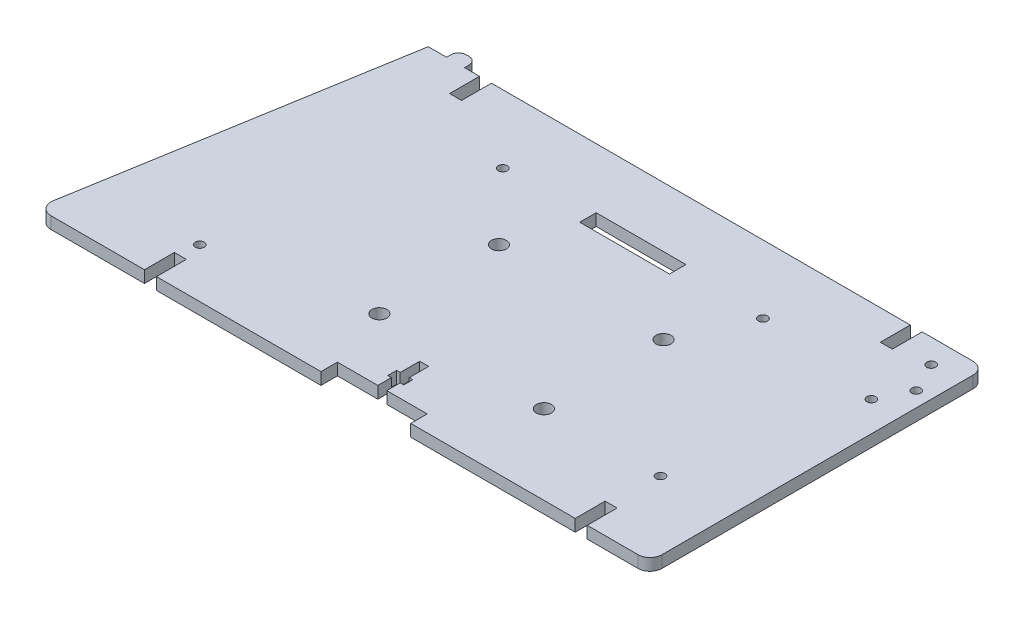
SolidWorks part; units mm, degrees
ref_plane "Front Plane" through (0, 0, 0) normal (0, 0, 1) x (1, 0, 0)
ref_plane "Top Plane" through (0, 0, 0) normal (0, 1, 0) x (1, 0, 0)
ref_plane "Right Plane" through (0, 0, 0) normal (1, 0, 0) x (0, 0, -1)
sketch "Sketch1" plane through (0, 0, 0) normal (0, 1, 0) x (1, 0, 0)
  line L0 (158.5, 0) -> (180, 0)
  line L1 (0, 0) -> (36, 0)
  line L2 (40, 112) -> (180, 112)
  line L3 (18.8632, 112) -> (25, 112)
  line L4 (205, 0) -> (205, 112)
  line L5 (184, 0) -> (205, 0)
  line L6 (95, 0) -> (95, 5.5)
  line L7 (95, 5.5) -> (108.5, 5.5)
  line L8 (125, 0) -> (125, 5.5)
  line L9 (40, 0) -> (95, 0)
  line L10 (111.5, 5.5) -> (125, 5.5)
  line L11 (31, 112) -> (36, 112)
  line L12 (108.5, 5.5) -> (108.5, 10)
  line L13 (108.5, 19.5) -> (111.5, 19.5)
  line L14 (111.5, 5.5) -> (111.5, 10)
  line L15 (107.3, 13) -> (108.5, 13)
  line L16 (107.3, 13) -> (107.3, 10)
  line L17 (107.3, 10) -> (108.5, 10)
  line L18 (112.7, 13) -> (112.7, 10)
  line L19 (111.5, 10) -> (112.7, 10)
  line L20 (111.5, 13) -> (112.7, 13)
  line L21 (125, 0) -> (155.5, 0)
  line L22 (18.8632, 112) -> (0, 0)
  line L23 (180, 0) -> (180, 10)
  line L24 (180, 10) -> (184, 10)
  line L25 (184, 0) -> (184, 10)
  line L26 (184, 112) -> (205, 112)
  line L27 (40, 0) -> (40, 10)
  line L28 (40, 10) -> (36, 10)
  line L29 (36, 0) -> (36, 10)
  line L30 (155.5, 0) -> (158.5, 0)
  line L31 (36, 112) -> (36, 102)
  line L32 (36, 102) -> (40, 102)
  line L33 (40, 112) -> (40, 102)
  line L34 (108.5, 13) -> (108.5, 19.5)
  line L35 (180, 112) -> (180, 102)
  line L36 (180, 102) -> (184, 102)
  line L37 (184, 112) -> (184, 102)
  line L38 (95, 92) -> (125, 92)
  line L39 (95, 92) -> (95, 86.5)
  line L40 (95, 86.5) -> (125, 86.5)
  line L41 (125, 92) -> (125, 86.5)
  line L42 (111.5, 13) -> (111.5, 19.5)
  line L44 (31, 112) -> (31, 116)
  line L45 (31, 116) -> (25, 116)
  line L46 (25, 112) -> (25, 116)
  circle A0 centre (153.5, 89.25) radius 1.5
  circle A1 centre (66.5, 89.25) radius 1.5
  circle A2 centre (88, 66.5) radius 2.5
  circle A3 centre (88.0072, 26.5) radius 2.5
  circle A4 centre (143, 66.5) radius 2.5
  circle A5 centre (143.0072, 26.5) radius 2.5
  circle A6 centre (195, 104) radius 1.5
  circle A7 centre (195, 84) radius 1.5
  circle A8 centre (200, 94) radius 1.5
  circle A9 centre (182, 26.5) radius 1.5
  circle A10 centre (38, 16.5) radius 1.5
  dimension "D39" = 5
  dimension "D40" = 5
  dimension "D41" = 5
  dimension "D42" = 5
  dimension "D49" = 3
  dimension "D50" = 3
  dimension "D51" = 3
  dimension "D55" = 3
  dimension "D56" = 3
  dimension "D58" = 3
  dimension "D62" = 3
  dimension "D1" = 112
  dimension "D3" = 30
  dimension "D4" = 5.5
  dimension "D5" = 80
  dimension "D6" = 3
  dimension "D7" = 14
  dimension "D8" = 13.5
  dimension "D9" = 1.2
  dimension "D10" = 5.4
  dimension "D11" = 4.5
  dimension "D12" = 3
  dimension "D13" = 55
  dimension "D14" = 4
  dimension "D15" = 10
  dimension "D16" = 4
  dimension "D17" = 55
  dimension "D18" = 10
  dimension "D19" = 4
  dimension "D20" = 10
  dimension "D21" = 55
  dimension "D22" = 17.1368
  dimension "D23" = 30
  dimension "D24" = 5.5
  dimension "D25" = 81
  dimension "D26" = 80
  dimension "D27" = 28.5
  dimension "D28" = 28.5
  dimension "D29" = 2.75
  dimension "D30" = 2.75
  dimension "D31" = 205
  dimension "D32" = 40
  dimension "D33" = 20
  dimension "D34" = 7
  dimension "D35" = 55
  dimension "D36" = 55
  dimension "D37" = 40
  dimension "D38" = 20
  dimension "D43" = 8
  dimension "D44" = 10
  dimension "D45" = 5
  dimension "D46" = 10
  dimension "D47" = 20
  dimension "D48" = 18
  dimension "D52" = 5
  dimension "D53" = 6
  dimension "D54" = 4
  dimension "D57" = 2
  dimension "D59" = 6.5
  dimension "D60" = 16.5
  dimension "D61" = 2
extrude "Boss-Extrude1" add sketch "Sketch1" along normal blind 4
fillet "Fillet1" radius 4 1 edges at (0, 2, 0)
fillet "Fillet3" radius 4 1 edges at (205, 2, -112)
fillet "Fillet4" radius 4 1 edges at (205, 2, 0)
fillet "Fillet5" radius 2.5 2 edges at (31, 2, -116) (25, 2, -116)
